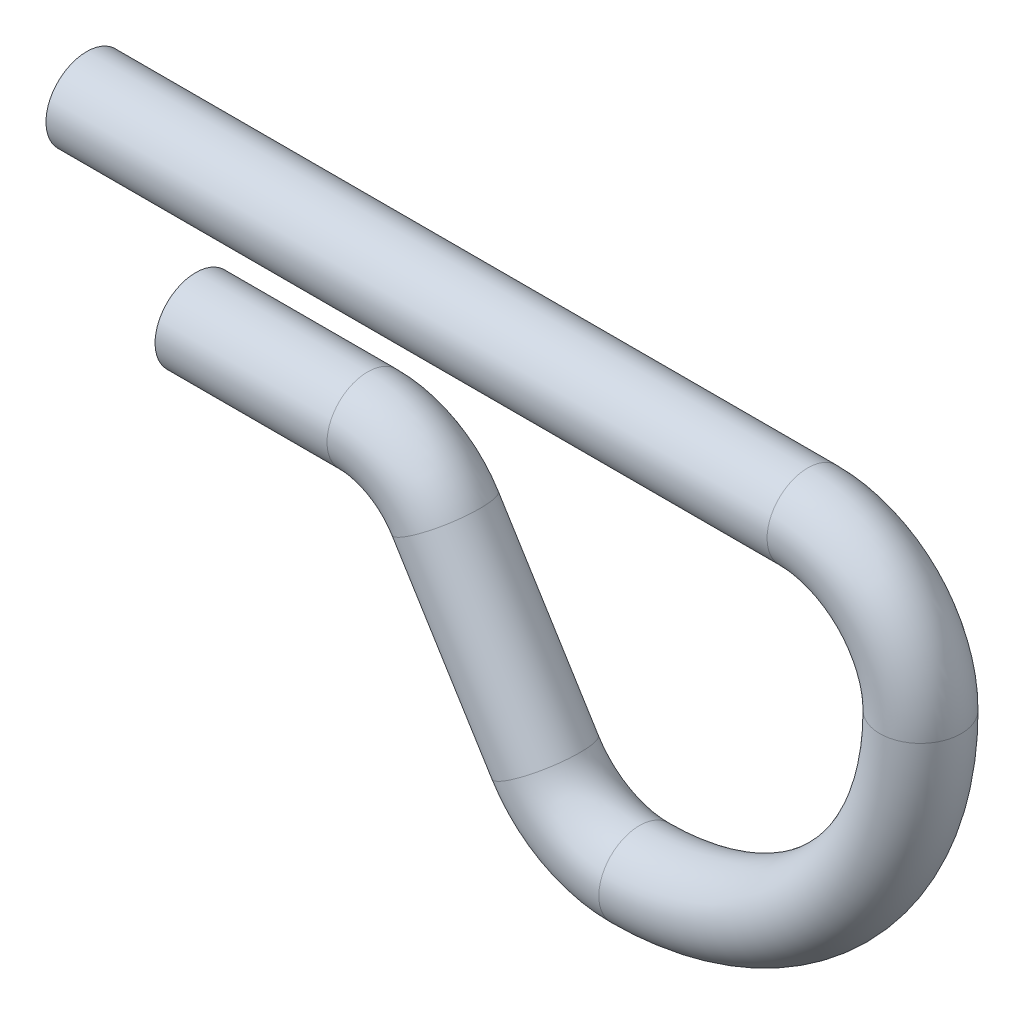
SolidWorks part; units mm, degrees
ref_plane "Front Plane" through (0, 0, 0) normal (0, 0, 1) x (1, 0, 0)
ref_plane "Top Plane" through (0, 0, 0) normal (0, 1, 0) x (1, 0, 0)
ref_plane "Right Plane" through (0, 0, 0) normal (1, 0, 0) x (0, 0, -1)
sketch "Sketch1" plane through (0, 0, 0) normal (0, 0, 1) x (1, 0, 0)
  line L0 (0, 0) -> (23.622, 0)
  line L1 (34.2679, -5.9269) -> (48.006, -28.0942)
  line L2 (84.074, 18.796) -> (-14.986, 18.796)
  arc A0 (23.622, 0) -> (34.2679, -5.9269) centre (23.622, -12.5246) cw
  arc A1 (48.006, -28.0942) -> (60.96, -35.306) centre (60.96, -20.066) ccw
  arc A2 (60.96, -35.306) -> (99.568, 3.302) centre (60.96, 3.302) ccw
  arc A3 (84.074, 18.796) -> (99.568, 3.302) centre (84.074, 3.302) cw
  point P12 (37.6837, 0)
  point P13 (41.0622, -9.7635)
  point P15 (0, 0)
  dimension "D2" = 84.074
  dimension "D3" = 38.608
  dimension "D7" = 15.494
  dimension "D1" = 99.06
  dimension "D4" = 23.114
  dimension "D5" = 60.452
  dimension "D6" = 36.068
  dimension "D8" = 23.368
  dimension "D9" = 18.796
  dimension "D10" = 23.114
  dimension "D11" = 23.368
sweep "Sweep1" add path "Sketch1" circular profile diameter 11.176 parameters "D3"=11.176
